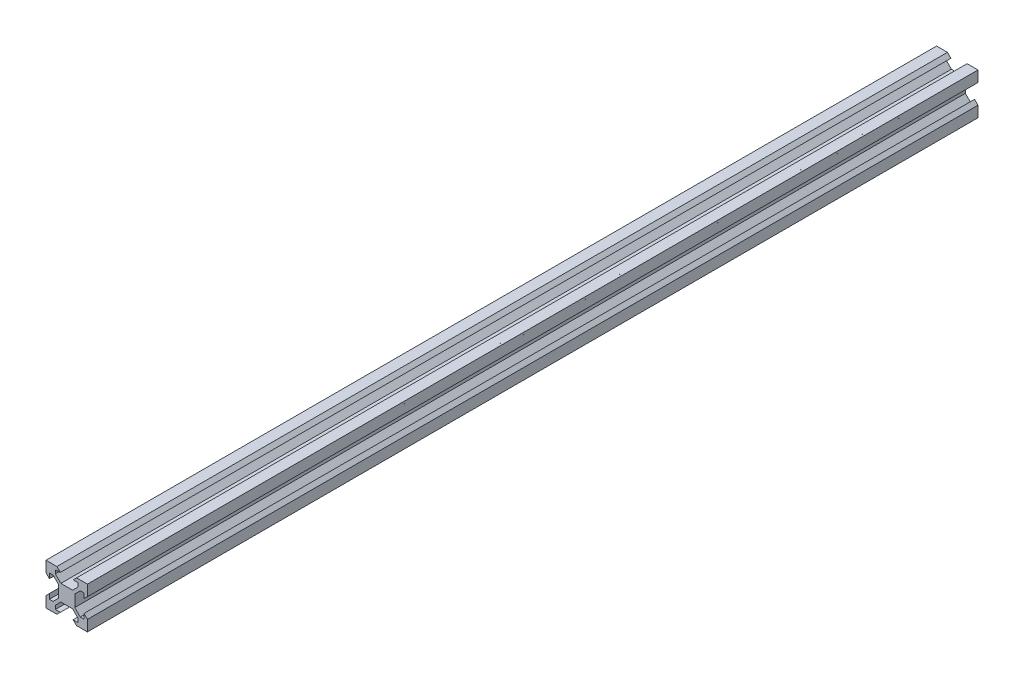
SolidWorks part; units mm, degrees
ref_plane "Front Plane" through (0, 0, 0) normal (0, 0, 1) x (1, 0, 0)
ref_plane "Top Plane" through (0, 0, 0) normal (0, 1, 0) x (1, 0, 0)
ref_plane "Right Plane" through (0, 0, 0) normal (1, 0, 0) x (0, 0, -1)
sketch "Sketch1" plane through (0, 0, 0) normal (0, 0, 1) x (1, 0, 0)
  line L88 (2.8343, 3.894) -> (-2.8343, 3.894)
  line L89 (-2.8343, 3.894) -> (-5.5, 6.5588)
  line L90 (-5.5, 6.5588) -> (-5.5, 8.3491)
  line L91 (-5.5, 8.3491) -> (-3.1, 8.3491)
  line L92 (-3.1, 8.3491) -> (-4.75, 9.9986)
  line L93 (-4.75, 9.9986) -> (-10, 9.9986)
  line L94 (-10, 9.9986) -> (-10, 4.747)
  line L95 (-10, 4.747) -> (-8.35, 3.0975)
  line L96 (-8.35, 3.0975) -> (-8.3507, 5.4975)
  line L97 (-8.3507, 5.4975) -> (-6.5605, 5.498)
  line L98 (-6.5605, 5.498) -> (-3.8948, 2.8332)
  line L99 (-3.8948, 2.8332) -> (-3.8948, -2.8332)
  line L100 (-3.8948, -2.8332) -> (-6.5605, -5.498)
  line L101 (-6.5605, -5.498) -> (-8.3507, -5.4975)
  line L102 (-8.3507, -5.4975) -> (-8.35, -3.0975)
  line L103 (-8.35, -3.0975) -> (-10, -4.747)
  line L104 (-10, -4.747) -> (-10, -9.9986)
  line L105 (-10, -9.9986) -> (-4.75, -9.9986)
  line L106 (-4.75, -9.9986) -> (-3.1, -8.3491)
  line L107 (-3.1, -8.3491) -> (-5.5, -8.3491)
  line L108 (-5.5, -8.3491) -> (-5.5, -6.5588)
  line L109 (-5.5, -6.5588) -> (-2.8343, -3.894)
  line L110 (-2.8343, -3.894) -> (2.8343, -3.894)
  line L111 (2.8343, -3.894) -> (5.5, -6.5588)
  line L112 (5.5, -6.5588) -> (5.5, -8.3491)
  line L113 (5.5, -8.3491) -> (3.1, -8.3491)
  line L114 (3.1, -8.3491) -> (4.75, -9.9986)
  line L115 (4.75, -9.9986) -> (10, -9.9986)
  line L116 (10, -9.9986) -> (10, -4.747)
  line L117 (10, -4.747) -> (8.35, -3.0975)
  line L118 (8.35, -3.0975) -> (8.3507, -5.4975)
  line L119 (8.3507, -5.4975) -> (6.5605, -5.498)
  line L120 (6.5605, -5.498) -> (3.8948, -2.8332)
  line L121 (3.8948, -2.8332) -> (3.8948, 2.8332)
  line L122 (3.8948, 2.8332) -> (6.5605, 5.498)
  line L123 (6.5605, 5.498) -> (8.3507, 5.4975)
  line L124 (8.3507, 5.4975) -> (8.35, 3.0975)
  line L125 (8.35, 3.0975) -> (10, 4.747)
  line L126 (10, 4.747) -> (10, 9.9986)
  line L127 (10, 9.9986) -> (4.75, 9.9986)
  line L128 (4.75, 9.9986) -> (3.1, 8.3491)
  line L129 (3.1, 8.3491) -> (5.5, 8.3491)
  line L130 (5.5, 8.3491) -> (5.5, 6.5588)
  line L131 (5.5, 6.5588) -> (2.8343, 3.894)
  dimension "D2" = 5.25
  dimension "D3" = 19.9971
  dimension "D4" = 20
extrude "Boss-Extrude1" add sketch "Sketch1" along normal blind 430
